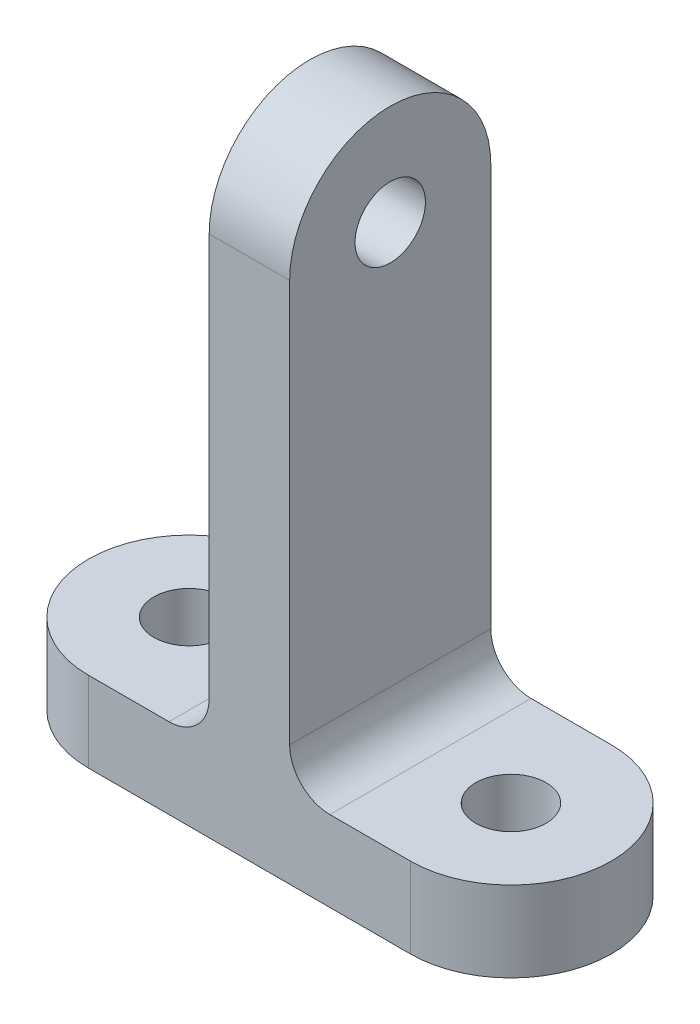
SolidWorks part; units mm, degrees
ref_plane "Front Plane" through (0, 0, 0) normal (0, 0, 1) x (1, 0, 0)
ref_plane "Top Plane" through (0, 0, 0) normal (0, 1, 0) x (1, 0, 0)
ref_plane "Right Plane" through (0, 0, 0) normal (1, 0, 0) x (0, 0, -1)
sketch "Sketch1" plane through (0, 0, 0) normal (0, 1, 0) x (1, 0, 0)
  line L0 (-8, 5) -> (8, 5)
  line L1 (8, -5) -> (-8, -5)
  circle A0 centre (-8, 0) radius 1.75
  circle A1 centre (8, 0) radius 1.75
  circle A2 centre (-8, 0) radius 5
  circle A3 centre (8, 0) radius 5
  dimension "D1" = 3.5
  dimension "D2" = 3.5
  dimension "D5" = 10
  dimension "D6" = 10
  dimension "D3" = 8
  dimension "D4" = 8
extrude "Boss-Extrude1" add sketch "Sketch1" along normal blind 4 contours A2 A0 | A3 L0 A2 L1 | A3 A1
sketch "Sketch2" plane through (0, 4, 0) normal (0, 1, 0) x (1, 0, 0)
  line L0 (8, -5) -> (-8, -5) construction
  line L1 (2, 5) -> (-2, 5)
  line L2 (2, 5) -> (2, -5)
  line L3 (2, -5) -> (-2, -5)
  line L4 (-2, 5) -> (-2, -5)
  line L5 (2, 5) -> (-2, -5) construction
  line L6 (2, -5) -> (-2, 5) construction
  point P0 (0, 0)
  dimension "D1" = 4
extrude "Boss-Extrude2" add sketch "Sketch2" along normal blind 27
sketch "Sketch3" plane through (2, 0, 0) normal (1, 0, 0) x (0, 0, -1)
  line L0 (-5, 31) -> (5, 31) construction
  line L5 (-5, 4) -> (5, 4)
  line L6 (5, 4) -> (5, 31)
  line L7 (5, 31) -> (-5, 31)
  line L8 (-5, 31) -> (-5, 4)
  line L9 (-5, 4) -> (5, 4)
  line L10 (5, 4) -> (5, 31)
  line L11 (5, 31) -> (-5, 31)
  line L12 (-5, 31) -> (-5, 4)
  circle A0 centre (0, 26) radius 1.75
  circle A1 centre (0, 26) radius 5
  line M9 (5, 31) -> (-5, 31)
  line M10 (-5, 31) -> (-5, 4)
  dimension "D2" = 3.5
  dimension "D1" = 5
  dimension "D3" = 0
extrude "Cut-Extrude1" cut sketch "Sketch3" against normal up to surface (4 mm away) contours A1 L11 M10 | A1 L10 M9 | A0 up to face at (-2, 17.5, 0)
fillet "Fillet1" radius 2 1 edges at (2, 4, 0)
fillet "Fillet2" radius 2 1 edges at (-2, 4, 0)
